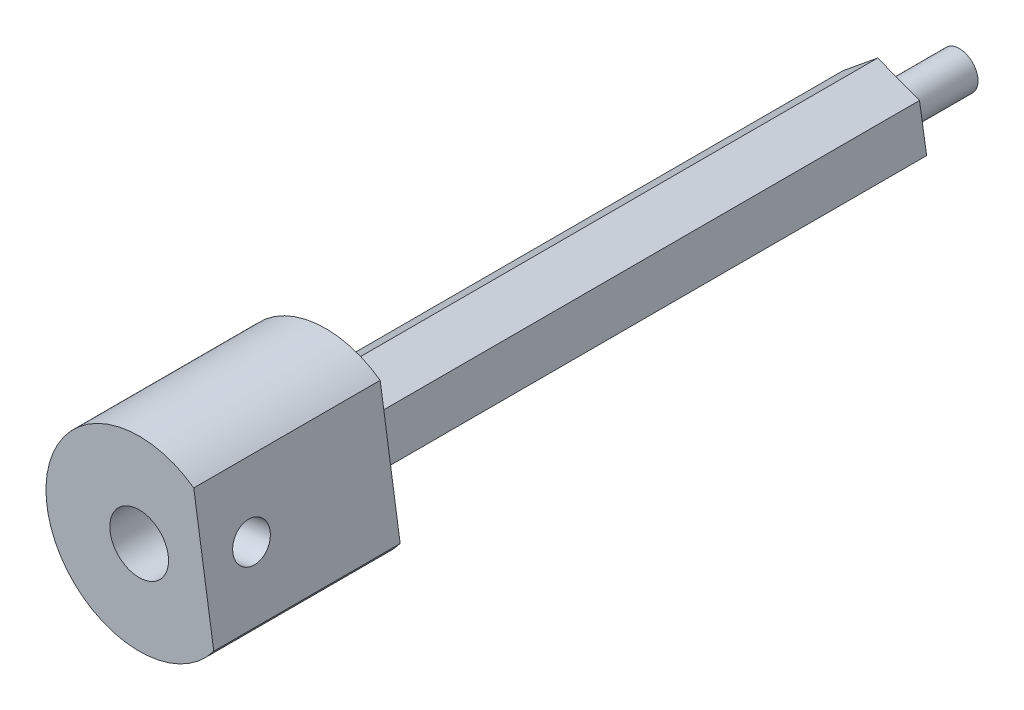
SolidWorks part; units mm, degrees
ref_plane "Front Plane" through (0, 0, 0) normal (0, 0, 1) x (1, 0, 0)
ref_plane "Top Plane" through (0, 0, 0) normal (0, 1, 0) x (1, 0, 0)
ref_plane "Right Plane" through (0, 0, 0) normal (1, 0, 0) x (0, 0, -1)
sketch "Sketch1" plane through (0, 0, 0) normal (0, 0, 1) x (1, 0, 0)
  circle A0 centre (0, 0) radius 6.35
  dimension "D1" = 12.7
extrude "Boss-Extrude1" add sketch "Sketch1" along normal blind 12.7
sketch "Sketch3" plane through (0, 0, 0) normal (0, 0, -1) x (-1, 0, 0)
  line L1 (0.4892, 3.0085) -> (-2.3608, 1.9279)
  line L2 (-2.3608, 1.9279) -> (-2.85, -1.0806)
  line L3 (-2.85, -1.0806) -> (-0.4892, -3.0085)
  line L4 (-0.4892, -3.0085) -> (2.3608, -1.9279)
  line L5 (2.3608, -1.9279) -> (2.85, 1.0806)
  line L6 (2.85, 1.0806) -> (0.4892, 3.0085)
  circle A0 centre (0, 0) radius 2.6396 construction
  dimension "D1" = 2.85
extrude "Boss-Extrude2" add sketch "Sketch3" along normal blind 38.1
sketch "Sketch8" plane through (0, 0, -38.1) normal (0, 0, -1) x (-1, 0, 0)
  circle A0 centre (0, 0) radius 1.27
  dimension "D1" = 2.54
extrude "Boss-Extrude3" add sketch "Sketch8" along normal blind 5.08
sketch "Sketch9" plane through (0, 0, 0) normal (0, 0, -1) x (-1, 0, 0)
  line L0 (-5.082, -3.8073) -> (-3.7185, 5.1474)
  line L1 (-5.082, -3.8073) -> (-7.5289, -3.4347)
  line L2 (-3.7185, 5.1474) -> (-6.1653, 5.5199)
  line L3 (-7.5289, -3.4347) -> (-6.1653, 5.5199)
  circle A0 centre (0, 0) radius 6.35 construction
extrude "Cut-Extrude1" cut sketch "Sketch9" against normal blind 13.97
sketch "Sketch10" plane through (4.4003, 0.67, 0) normal (0.9886, 0.1505, 0) x (0, 0, -1)
  line L0 (-12.7, 0) -> (0, 0) construction
  line L1 (-12.7, 4.5289) -> (-12.7, -4.5289) construction
  line L2 (-6.35, 0) -> (-6.35, 4.5289) construction
  line L3 (-12.7, 4.5289) -> (0, 4.5289) construction
  circle A0 centre (-9.4464, 0) radius 1.27
  dimension "D1" = 2.54
extrude "Cut-Extrude2" cut sketch "Sketch10" against normal blind 5.08
sketch "Sketch11" plane through (0, 0, 12.7) normal (0, 0, 1) x (1, 0, 0)
  circle A0 centre (0, 0) radius 2
  dimension "D1" = 4
extrude "Cut-Extrude3" cut sketch "Sketch11" against normal blind 6.35
